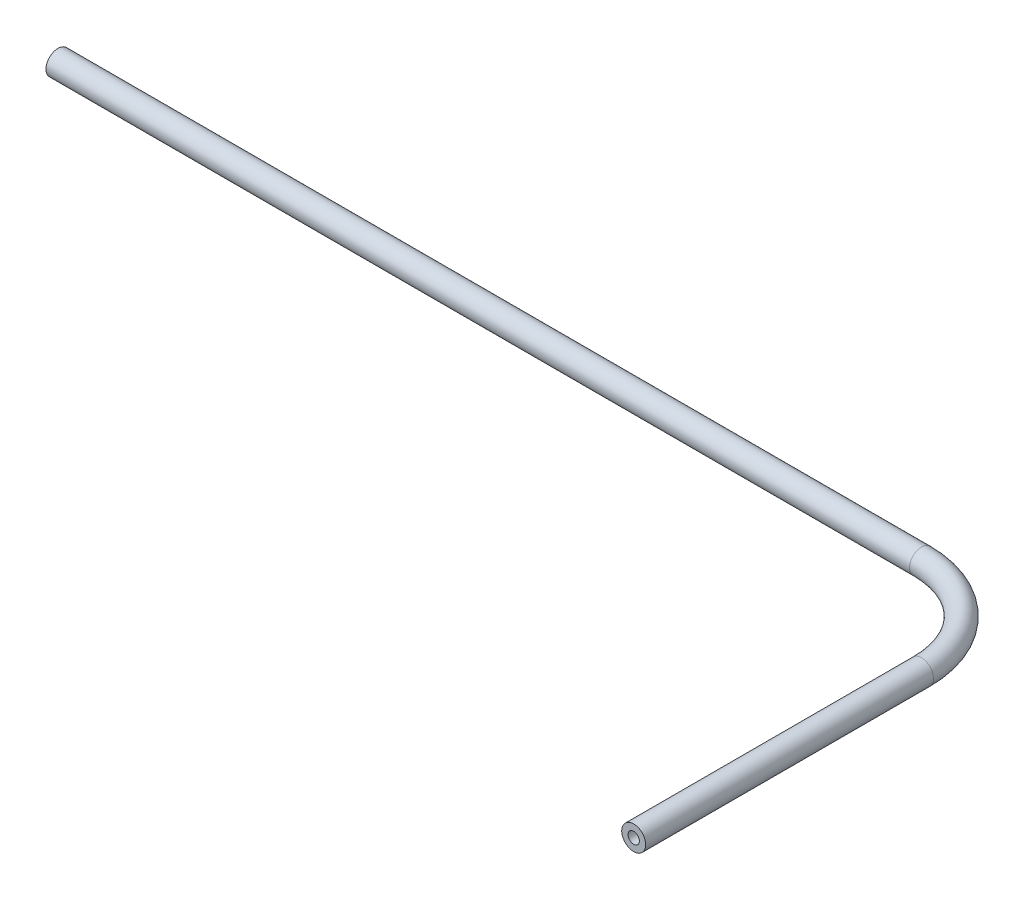
SolidWorks part; units mm, degrees
ref_plane "Front Plane" through (0, 0, 0) normal (0, 0, 1) x (1, 0, 0)
ref_plane "Top Plane" through (0, 0, 0) normal (0, 1, 0) x (1, 0, 0)
ref_plane "Right Plane" through (0, 0, 0) normal (1, 0, 0) x (0, 0, -1)
sketch "Sketch1" plane through (0, 0, 0) normal (0, 1, 0) x (1, 0, 0)
  line L0 (-254, 0) -> (-25.4, 0)
  line L1 (-55, 0) -> (55, 0) construction
  line L2 (0, -25.4) -> (0, -101.6)
  line L3 (0, -55) -> (0, 55) construction
  arc A0 (0, -25.4) -> (-25.4, 0) centre (-25.4, -25.4) ccw
  dimension "D3" = 50.8
  dimension "D1" = 228.6
  dimension "D2" = 76.2
ref_plane "Plane1" through (-254, 0, 0) normal (1, 0, 0) x (0, 0, -1)
sketch "Sketch2" plane through (-254, 0, 0) normal (1, 0, 0) x (0, 0, -1)
  circle A0 centre (0, 0) radius 3.175
  circle A1 centre (0, 0) radius 1.5
  dimension "D1" = 6.35
  dimension "D2" = 3
sweep "Sweep1" add profiles "Sketch2" path "Sketch1"
